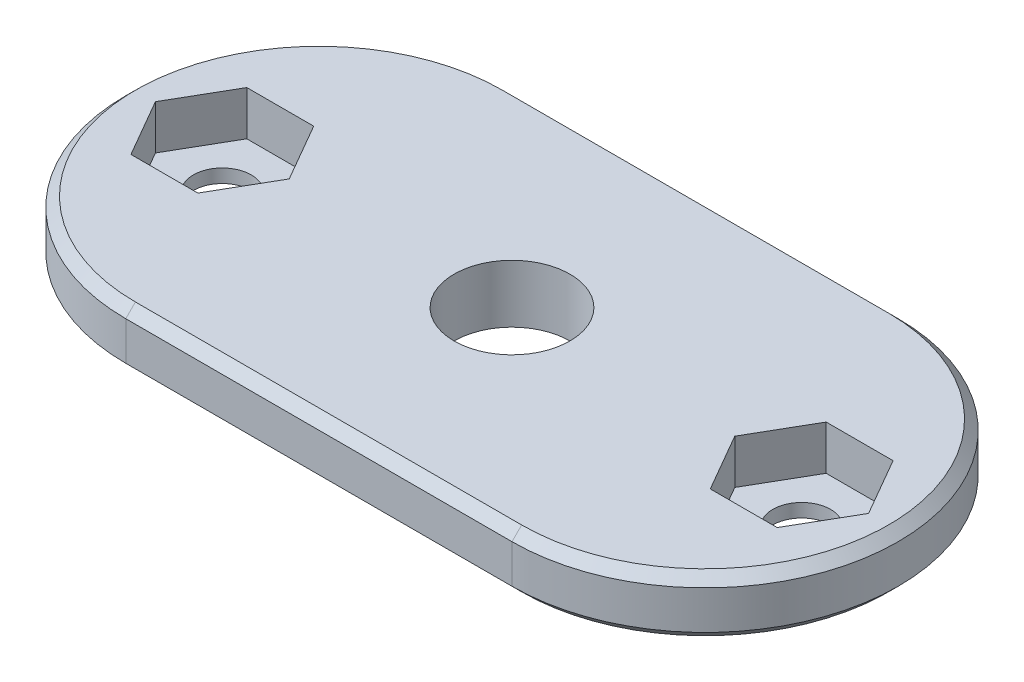
SolidWorks part; units mm, degrees
ref_plane "Front" through (0, 0, 0) normal (0, 0, 1) x (1, 0, 0)
ref_plane "Top" through (0, 0, 0) normal (0, 1, 0) x (1, 0, 0)
ref_plane "Right" through (0, 0, 0) normal (1, 0, 0) x (0, 0, -1)
other "Configuration Table"
sketch "Sketch2" plane through (0, 0, 0) normal (0, 1, 0) x (1, 0, 0)
  line L0 (0, 0) -> (20, 0) construction
  line L1 (0, 10) -> (20, 10)
  line L2 (0, -10) -> (20, -10)
  arc A0 (0, 10) -> (0, -10) centre (0, 0) ccw
  arc A1 (20, -10) -> (20, 10) centre (20, 0) ccw
  point P3 (10, 0)
  dimension "D1" = 20
  dimension "D2" = 20
extrude "Boss-Extrude1" add sketch "Sketch2" along normal blind 3
sketch "Sketch3" plane through (0, 3, 0) normal (0, 1, 0) x (1, 0, 0)
  line L0 (0, 0) -> (19.0893, 0) construction
  line L1 (10, 10) -> (10, -10) construction
  line L6 (20, 10) -> (0, 10) construction
  line L7 (0, -10) -> (20, -10) construction
  circle A0 centre (10, 0) radius 3
  point P1 (9.9175, -0.2578)
  point P3 (10.0863, 0)
  point P5 (10, 10)
  point P13 (9.5481, 0)
  point P14 (9.5481, 0)
  point P15 (0, 0)
  point P16 (9.5446, -0.2578)
  point P17 (0, 0)
  point P18 (9.4407, -1.4285)
  dimension "D2" = 6
sketch "Sketch13" plane through (0, 3, 0) normal (0, 1, 0) x (1, 0, 0)
  line L0 (-10, 0) -> (30, 0) construction
  arc A0 (0, 10) -> (0, -10) centre (0, 0) ccw construction
  arc A1 (20, -10) -> (20, 10) centre (20, 0) ccw construction
  point P8 (-5, 0)
  point P9 (25, 0)
  dimension "D1" = 5
  dimension "D2" = 5
hole_wizard "M3x0.5 Tapped Hole1" positions "Sketch14" profile "Sketch15" tap size "M3x0.5" standard "ANSI Metric" end condition through all
sketch "Sketch14" plane through (0, 3, 0) normal (0, 1, 0) x (1, 0, 0)
  point P0 (-5, 0)
  point P3 (25, 0)
sketch "Sketch15" plane through (-5, 3, 0) normal (1, 0, 0) x (0, 0, 1)
  line L0 (0, 0) -> (0, 3)
  line L1 (0, 3) -> (1.5, 3)
  line L2 (1.5, 3) -> (1.5, 0.025)
  line L3 (1.5, 0.025) -> (1.525, 0)
  line L5 (1.525, 0) -> (0, 0)
  line L6 (-1.5, 0.025) -> (-1.525, 0) construction
  line L11 (0, -6.35) -> (0, 107.95) construction
  dimension "Thread Major Dia." = 3
  dimension "Thru Tap Drill Depth" = 3
  dimension "Near C'Sink Dia." = 3.05
  dimension "Near C'Sink Angle" = 90
chamfer "Chamfer1" distance 0.5 angle 45 8 edges at (30, 3, 0) (10, 3, -10) (10, 3, 10) (-10, 3, 0) (10, 0, 10) (30, 0, 0) (-10, 0, 0) (10, 0, -10)
extrude "Cut-Extrude1" cut sketch "Sketch3" against normal through all contours A0
sketch "Sketch16" plane through (0, 3, 0) normal (0, 1, 0) x (1, 0, 0)
  line L0 (-10, 0) -> (30, 0) construction
  line L1 (-1.5359, 0) -> (-3.2679, 3)
  line L2 (-3.2679, 3) -> (-6.7321, 3)
  line L3 (-6.7321, 3) -> (-8.4641, 0)
  line L4 (-8.4641, 0) -> (-6.7321, -3)
  line L5 (-6.7321, -3) -> (-3.2679, -3)
  line L6 (-3.2679, -3) -> (-1.5359, 0)
  line L7 (21.5359, 0) -> (23.2679, -3)
  line L8 (23.2679, -3) -> (26.7321, -3)
  line L9 (26.7321, -3) -> (28.4641, 0)
  line L10 (28.4641, 0) -> (26.7321, 3)
  line L11 (26.7321, 3) -> (23.2679, 3)
  line L12 (23.2679, 3) -> (21.5359, 0)
  circle A0 centre (-5, 0) radius 3 construction
  circle A1 centre (25, 0) radius 3 construction
  point P10 (-1.5359, 0)
  point P21 (23.2981, 3)
  dimension "D1" = 6
  dimension "D2" = 6
extrude "Cut-Extrude2" cut sketch "Sketch16" against normal blind 2.3
